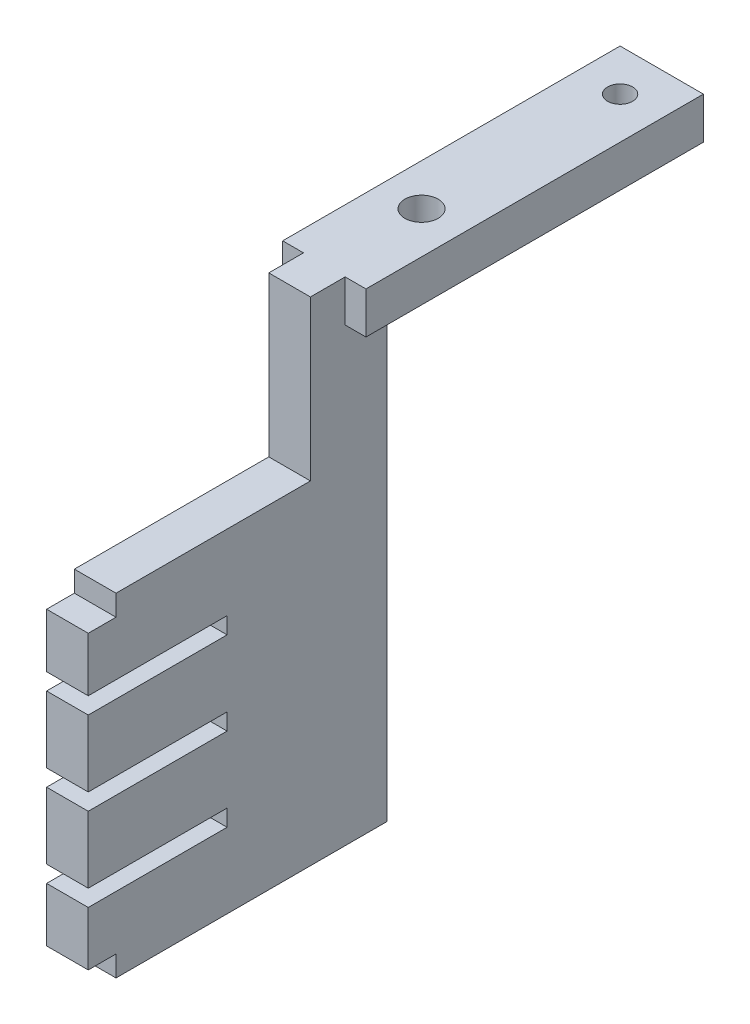
SolidWorks part; units mm, degrees
ref_plane "Front Plane" through (0, 0, 0) normal (0, 0, 1) x (1, 0, 0)
ref_plane "Top Plane" through (0, 0, 0) normal (0, 1, 0) x (1, 0, 0)
ref_plane "Right Plane" through (0, 0, 0) normal (1, 0, 0) x (0, 0, -1)
sketch "Sketch1" plane through (0, 0, 0) normal (0, 0, 1) x (1, 0, 0)
  line L0 (14.8, 20.475) -> (20.8, 20.475)
  line L1 (20.8, 20.475) -> (20.8, 23.475)
  line L2 (20.8, 23.475) -> (14.8, 23.475)
  line L3 (14.8, 23.475) -> (14.8, 20.475)
extrude "Boss-Extrude1" add sketch "Sketch1" along normal blind 24.3 from offset 7.2
sketch "Sketch2" plane through (0, 0, 0) normal (0, 0, 1) x (1, 0, 0)
  line L0 (16.3, -12) -> (19.3, -12)
  line L1 (19.3, -12) -> (19.3, 23.475)
  line L2 (19.3, 23.475) -> (16.3, 23.475)
  line L3 (16.3, 23.475) -> (16.3, -12)
extrude "Boss-Extrude2" add sketch "Sketch2" along normal blind 21.5 from offset 28.5
sketch "Sketch3" plane through (0, 0, 0) normal (0, 1, 0) x (1, 0, 0)
  circle A0 centre (17.8, -24.5) radius 1.2
  circle A1 centre (17.8, -10.2) radius 0.9
extrude "Cut-Extrude1" cut sketch "Sketch3" against normal through all and the other way through all
sketch "Sketch4" plane through (0, 0, 0) normal (1, 0, 0) x (0, 0, -1)
  line L0 (-40, -6.6) -> (-40, -5.4)
  line L1 (-40, -5.4) -> (-51, -5.4)
  line L2 (-51, -5.4) -> (-51, -6.6)
  line L3 (-51, -6.6) -> (-40, -6.6)
  line L4 (-40, -0.6) -> (-40, 0.6)
  line L5 (-40, 0.6) -> (-51, 0.6)
  line L6 (-51, 0.6) -> (-51, -0.6)
  line L7 (-51, -0.6) -> (-40, -0.6)
  line L8 (-40, 5.4) -> (-40, 6.6)
  line L9 (-40, 6.6) -> (-51, 6.6)
  line L10 (-51, 6.6) -> (-51, 5.4)
  line L11 (-51, 5.4) -> (-40, 5.4)
  line L12 (-34, 12) -> (-34, 24.475)
  line L13 (-34, 24.475) -> (-51, 24.475)
  line L14 (-51, 24.475) -> (-51, 12)
  line L15 (-51, 12) -> (-34, 12)
extrude "Cut-Extrude2" cut sketch "Sketch4" against normal through all and the other way through all
sketch "Sketch5" plane through (0, 0, 0) normal (1, 0, 0) x (0, 0, -1)
  line L0 (-48, -13) -> (-48, -10.5)
  line L1 (-48, -10.5) -> (-51, -10.5)
  line L2 (-51, -10.5) -> (-51, -13)
  line L3 (-51, -13) -> (-48, -13)
  line L4 (-48, 10.5) -> (-48, 13)
  line L5 (-48, 13) -> (-51, 13)
  line L6 (-51, 13) -> (-51, 10.5)
  line L7 (-51, 10.5) -> (-48, 10.5)
extrude "Cut-Extrude3" cut sketch "Sketch5" against normal through all and the other way through all
